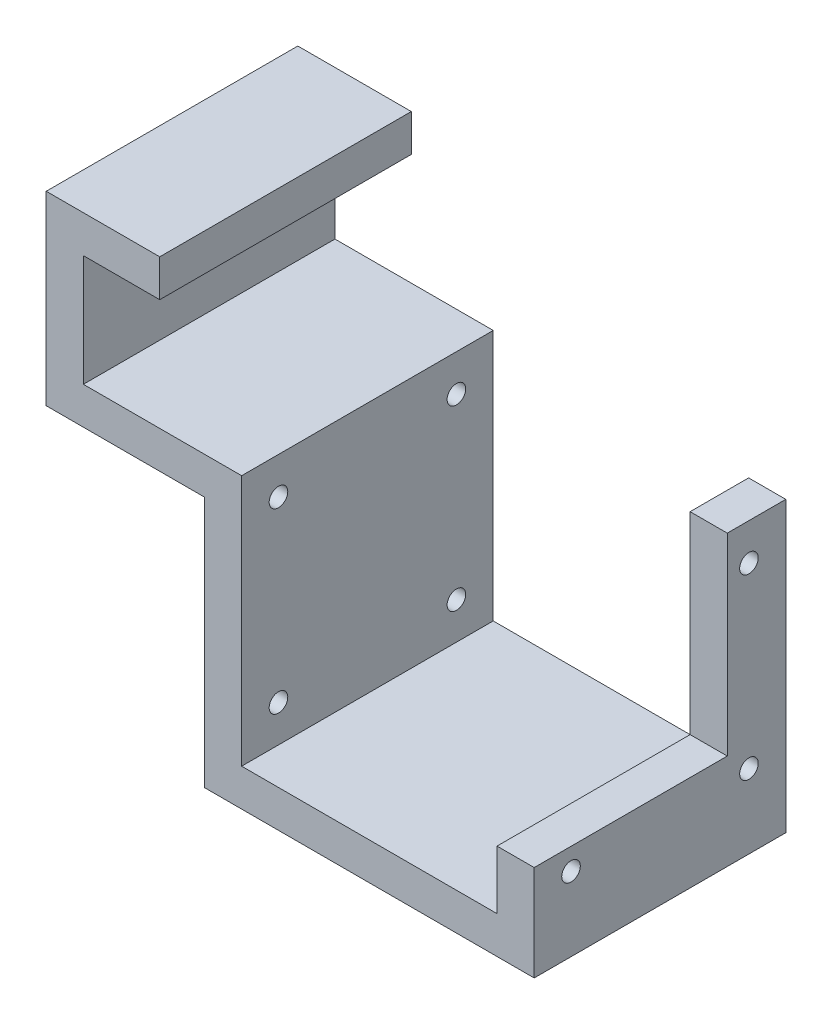
SolidWorks part; units mm, degrees
ref_plane "Front Plane" through (0, 0, 0) normal (0, 0, 1) x (1, 0, 0)
ref_plane "Top Plane" through (0, 0, 0) normal (0, 1, 0) x (1, 0, 0)
ref_plane "Right Plane" through (0, 0, 0) normal (1, 0, 0) x (0, 0, -1)
sketch "Sketch1" plane through (0, 0, 0) normal (0, 0, 1) x (1, 0, 0)
  line L0 (-6.35, -27.85) -> (-6.35, 15.15)
  line L1 (-6.35, 15.15) -> (-33.4, 15.15)
  line L2 (-33.4, 15.15) -> (-33.4, 46.9)
  line L3 (-33.4, 46.9) -> (-14, 46.9)
  line L4 (-14, 46.9) -> (-14, 40.55)
  line L5 (-14, 40.55) -> (-27.05, 40.55)
  line L6 (-27.05, 40.55) -> (-27.05, 21.5)
  line L7 (-27.05, 21.5) -> (0, 21.5)
  line L8 (0, 21.5) -> (0, -21.5)
  line L9 (0, -21.5) -> (43.65, -21.5)
  line L12 (43.65, -21.5) -> (43.65, -27.85)
  line L13 (43.65, -27.85) -> (-6.35, -27.85)
  line L14 (-27.05, 40.55) -> (11.05, 40.55) construction
  line L15 (-27.05, 40.55) -> (-33.4, 46.9) construction
  line L16 (-27.05, 21.5) -> (-33.4, 15.15) construction
  line L17 (-6.35, 15.15) -> (0, 21.5) construction
  line L18 (0, -21.5) -> (-6.35, -27.85) construction
  line L20 (-27.05, 21.5) -> (-27.05, 40.55) construction
  line L21 (-27.05, 21.5) -> (277.75, 21.5) construction
  line L23 (33, -21.5) -> (0, -21.5) construction
  line L25 (-14, 43.09) -> (-14, 48.9) construction
  dimension "D1" = 6.35
  dimension "D2" = 50
extrude "Boss-Extrude1" add sketch "Sketch1" against normal up to surface (43 mm away) contours L6 L7 L8 L9 L12 L13 L0 L1 L2 L3 L4 L5
sketch "Sketch2" plane through (43.65, 0, 0) normal (1, 0, 0) x (0, 0, -1)
  line L0 (43, -27.85) -> (0, -27.85) construction
  line L1 (33, -27.85) -> (43, -27.85)
  line L2 (33, -27.85) -> (33, 21.5)
  line L3 (33, 21.5) -> (43, 21.5)
  line L4 (43, -27.85) -> (43, 21.5)
  line L5 (33, -27.85) -> (43, 21.5) construction
  line L6 (33, 21.5) -> (43, -27.85) construction
  line L7 (43, 21.5) -> (0, 21.5) construction
  line L9 (0, -27.85) -> (33, -27.85)
  line L10 (0, -27.85) -> (0, -11.5)
  line L11 (0, -11.5) -> (33, -11.5)
  line L12 (33, -27.85) -> (33, -11.5)
  line L13 (0, -27.85) -> (33, -11.5) construction
  line L14 (0, -11.5) -> (33, -27.85) construction
  circle A0 centre (21.5, 0) radius 11.5 construction
  circle A2 centre (6.2942, -15.2058) radius 1.5
  circle A3 centre (36.7058, -15.2058) radius 1.5
  circle A4 centre (36.7058, 15.2058) radius 1.5
  circle A5 centre (6.2942, -15.2058) radius 1.5 construction
  point P4 (38, -3.175)
  point P17 (16.5, -19.675)
  line M5 (0, -27.85) -> (43, -27.85)
  line M6 (43, -27.85) -> (43, -21.5)
  line M7 (43, -21.5) -> (0, -21.5)
  line M8 (0, -21.5) -> (0, -27.85)
extrude "Boss-Extrude2" add sketch "Sketch2" along normal blind 6.35 contours L2 M5 M7 M8 | L11 L10 L2 A2 M7 | L2 M5 M6 M7 | L4 L3 L2 A4 A3 M7
sketch "Sketch3" plane through (-6.35, 0, 0) normal (1, 0, 0) x (0, 0, -1)
  line L0 (0, 15.2058) -> (6.2942, 15.2058) construction
  line L1 (0, 21.5) -> (0, -21.5) construction
  circle A0 centre (6.2942, -15.2058) radius 1.5875
  circle A1 centre (6.2942, 15.2058) radius 1.5875
  circle A8 centre (36.7058, 15.2058) radius 1.5875
  circle A9 centre (36.7058, -15.2058) radius 1.5875
  dimension "D1" = 3.175
extrude "Cut-Extrude1" cut sketch "Sketch3" against normal blind 12.7 and the other way through all
